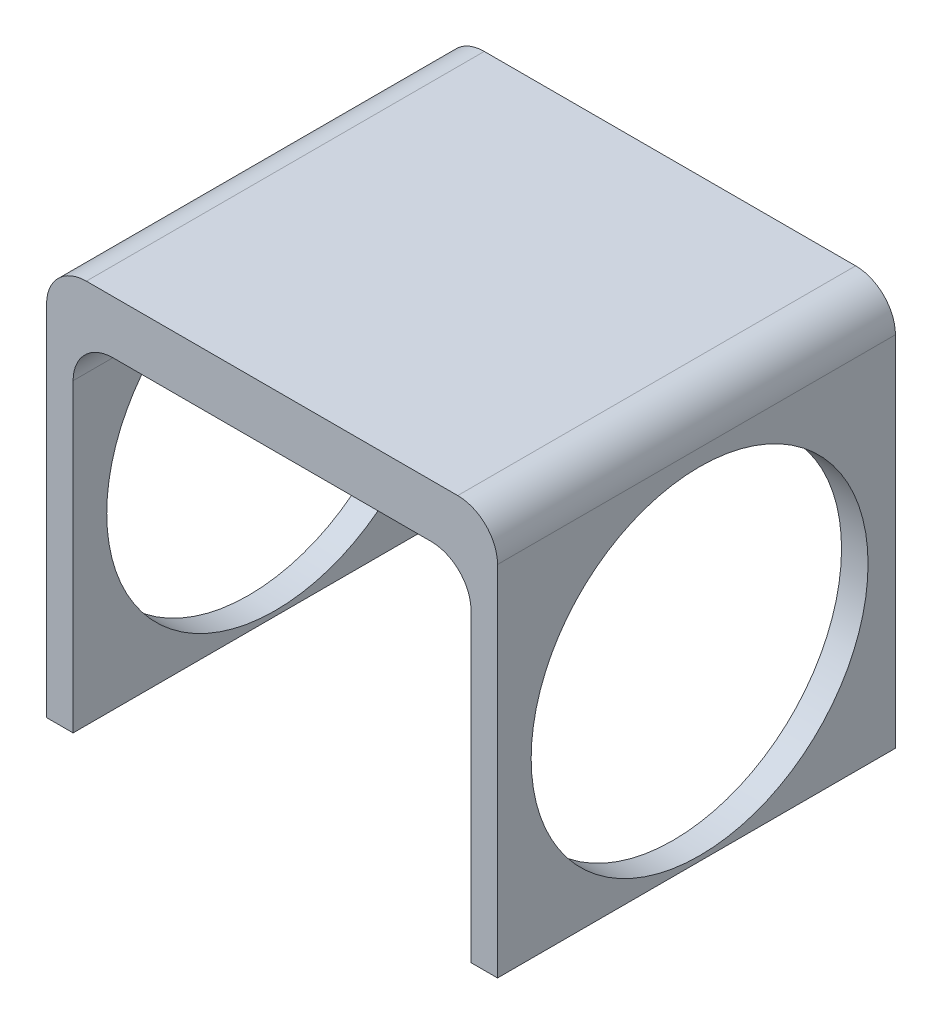
SolidWorks part; units mm, degrees
ref_plane "Plan de face" through (0, 0, 0) normal (0, 0, 1) x (1, 0, 0)
ref_plane "Plan de dessus" through (0, 0, 0) normal (0, 1, 0) x (1, 0, 0)
ref_plane "Plan de droite" through (0, 0, 0) normal (1, 0, 0) x (0, 0, -1)
sketch "Esquisse1" plane through (0, 0, 0) normal (0, 0, 1) x (1, 0, 0)
  line L0 (0, 0) -> (0, 27)
  line L1 (3, 30) -> (31, 30)
  line L2 (34, 27) -> (34, 0)
  line L3 (34, 0) -> (32, 0)
  line L4 (32, 0) -> (32, 23)
  line L5 (29, 26) -> (5, 26)
  line L6 (2, 23) -> (2, 0)
  line L7 (2, 0) -> (0, 0)
  arc A0 (0, 27) -> (3, 30) centre (3, 27) cw
  arc A1 (5, 26) -> (2, 23) centre (5, 23) ccw
  arc A2 (32, 23) -> (29, 26) centre (29, 23) ccw
  arc A3 (31, 30) -> (34, 27) centre (31, 27) cw
  point P11 (0, 30)
  point P14 (2, 26)
  point P17 (32, 26)
  point P20 (34, 30)
  dimension "D6" = 3
  dimension "D1" = 34
  dimension "D2" = 30
  dimension "D3" = 2
  dimension "D4" = 26
  dimension "D5" = 30
extrude "Boss.-Extru.1" add sketch "Esquisse1" along normal blind 30
hole_wizard "Perçage1" positions "Esquisse2" profile "Esquisse3" legacy end condition through all
sketch "Esquisse2" plane through (0, 0, 0) normal (-1, 0, 0) x (0, 0, 1)
  point P0 (14.7641, 13.0671)
sketch "Esquisse3" plane through (0, 13.0671, 14.7641) normal (0, 1, 0) x (0, 0, 1)
  line L0 (0, 0) -> (0, 34)
  line L1 (0, 34) -> (12.7, 34)
  line L2 (12.7, 34) -> (12.7, 0)
  line L3 (12.7, 0) -> (0, 0)
  line L4 (0, 110) -> (0, -10) construction
  dimension "Diamètre" = 25.4
  dimension "Profondeur" = 34
